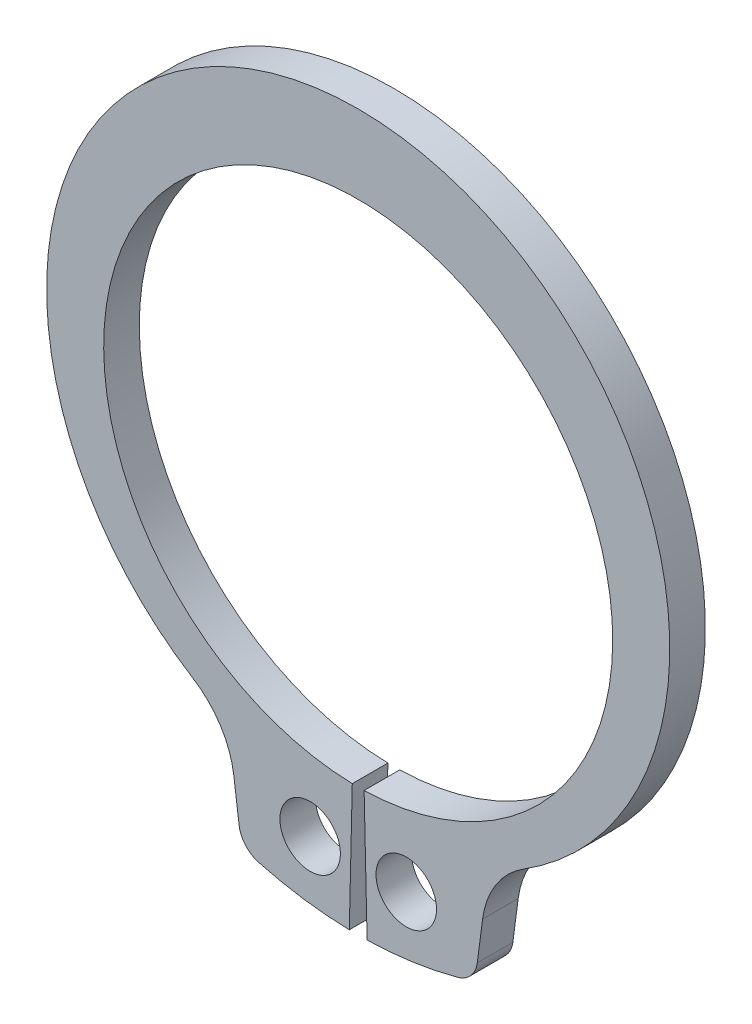
SolidWorks part; units mm, degrees
ref_plane "Plane1" through (0, 0, 0) normal (0, 0, 1) x (1, 0, 0)
ref_plane "Plane2" through (0, 0, 0) normal (0, 1, 0) x (1, 0, 0)
ref_plane "Plane3" through (0, 0, 0) normal (1, 0, 0) x (0, 0, -1)
sketch "Clipboard" plane through (0, 0, 0) normal (0, 0, 1) x (1, 0, 0)
  line L0 (0, 0) -> (2.2, 0)
  line L1 (0, 0) -> (0, 1.1)
  line L2 (0, 0) -> (0, -3.6)
  circle A0 centre (0, 0) radius 0.85
  circle A1 centre (0, 0) radius 7.5
  dimension "HoleDia" = 1.7
  dimension "ShaftDia" = 15
  dimension "LargeSection" = 2.2
  dimension "SmallSection" = 1.1
  dimension "LugSection" = 3.6
sketch "BodySke" plane through (0, 0, 0) normal (0, 0, 1) x (1, 0, 0)
  line L0 (-1.5431, 0) -> (1.5431, 0) construction
  line L1 (0, 0) -> (0, 9.35) construction
  line L2 (0.1663, -7.1481) -> (0.25, -10.7471)
  line L3 (-0.1663, -7.1481) -> (-0.25, -10.7471)
  line L4 (0, 0) -> (5.972, -8.9385) construction
  line L5 (0, 0) -> (-5.972, -8.9385) construction
  line L7 (3.4948, -8.6124) -> (3.3446, -9.7537)
  line L8 (-3.4948, -8.6124) -> (-3.3446, -9.7537)
  circle A0 centre (0, 0) radius 7.15 construction
  arc A1 (0.1663, -7.1481) -> (-0.1663, -7.1481) centre (0, 0) ccw
  arc A2 (4.5832, -6.8598) -> (-4.5832, -6.8598) centre (0, 0.5972) ccw construction
  arc A3 (0.25, -10.7471) -> (2.7961, -10.38) centre (0, 0) ccw
  arc A4 (4.6458, -6.8209) -> (3.4948, -8.6124) centre (5.972, -8.9385) ccw
  arc A5 (-3.4948, -8.6124) -> (-4.6458, -6.8209) centre (-5.972, -8.9385) ccw
  arc A6 (-2.7961, -10.38) -> (-0.25, -10.7471) centre (0, 0) ccw
  arc A7 (4.6458, -6.8209) -> (-4.6458, -6.8209) centre (0, 0.5972) ccw
  arc A8 (-3.5203, -8.4186) -> (3.5203, -8.4186) centre (0, 0) ccw construction
  circle A9 centre (1.35, -9.0246) radius 0.85
  circle A10 centre (-1.35, -9.0246) radius 0.85
  arc A11 (3.3446, -9.7537) -> (2.7961, -10.38) centre (2.601, -9.6558) cw
  arc A12 (-3.3446, -9.7537) -> (-2.7961, -10.38) centre (-2.601, -9.6558) ccw
  point P28 (3.2809, -10.2371)
  point P31 (-3.2809, -10.2371)
  dimension "GrooveDia" = 14.3
  dimension "D3" = 0.75
  dimension "LugRad" = 10.75
  dimension "HoleOffsetRad" = 9.125
  dimension "HoleDia" = 1.7
  dimension "D2" = 15
  dimension "LargeRad" = 9.35
  dimension "SmallRad" = 8.25
  dimension "Gap" = 0.5
  dimension "SmallAngle" = 67.496
  dimension "HoleSpacing" = 2.7
extrude "Body" add sketch "BodySke" against normal blind 1
sketch "NotSke" plane through (0, 0, 0) normal (0, 0, 1) x (1, 0, 0)
  line L0 (1.35, -8.1746) -> (1.35, -9.8746)
  line L1 (1.35, -9.8746) -> (-1.35, -9.8746)
  line L2 (-1.35, -9.8746) -> (-1.35, -8.1746)
  line L3 (-1.35, -8.1746) -> (1.35, -8.1746)
  circle A0 centre (1.35, -9.0246) radius 0.85 construction
  circle A1 centre (-1.35, -9.0246) radius 0.85 construction
extrude "Notch" [suppressed] cut sketch "NotSke" against normal through all
sketch "UnlSke" plane through (0, 0, 0) normal (0, 0, 1) x (1, 0, 0)
  line L0 (-2.5738, -10.4373) -> (-1.7119, -6.942)
  line L1 (2.5738, -10.4373) -> (1.7119, -6.942)
  arc A0 (1.7119, -6.942) -> (-1.7119, -6.942) centre (0, 0) ccw
  arc A1 (2.5738, -10.4373) -> (-2.5738, -10.4373) centre (0, 0) ccw
  arc A2 (0.25, -10.7471) -> (2.7961, -10.38) centre (0, 0) ccw construction
  arc A3 (0.1663, -7.1481) -> (-0.1663, -7.1481) centre (0, 0) ccw construction
  circle A4 centre (-1.35, -9.0246) radius 0.85 construction
  circle A5 centre (1.35, -9.0246) radius 0.85 construction
extrude "Unlug" [suppressed] add sketch "UnlSke" against normal through all
equation "' \"ShaftDia@Clipboard\" = 3"
equation "' \"Thickness@Body\" = 0.4"
equation "' \"GrooveDia@BodySke\" = 2.8"
equation "' \"LugSection@Clipboard\" = 1.9"
equation "' \"LargeSection@Clipboard\" = 0.8"
equation "' \"HoleDia@Clipboard\" = 1.0"
equation "' \"ShaftDia@Clipboard\" = 10"
equation "' \"Thickness@Body\" = 1.0"
equation "' \"GrooveDia@BodySke\" = 9.6"
equation "' \"LugSection@Clipboard\" = 3.3"
equation "' \"LargeSection@Clipboard\" = 1.8"
equation "' \"HoleDia@Clipboard\" = 1.5"
equation "\"SmallSection@Clipboard\" = \"LargeSection@Clipboard\" * 0.5"
equation "\"Gap@BodySke\" =  \"Thickness@Body\" / 2"
equation "\"LargeRad@BodySke\" =  \"GrooveDia@BodySke\" / 2 +  \"LargeSection@Clipboard\""
equation "\"SmallRad@BodySke\" =  \"GrooveDia@BodySke\" / 2 +  \"SmallSection@Clipboard\""
equation "\"LugRad@BodySke\" = \"GrooveDia@BodySke\" / 2 + \"LugSection@Clipboard\""
equation "\"HoleOffsetRad@BodySke\" = (  \"ShaftDia@Clipboard\" / 2 + \"LugRad@BodySke\" ) / 2"
equation "\"HoleSpacing@BodySke\" = \"Gap@BodySke\"  * 2 +  \"HoleDia@Clipboard\""
equation "\"HoleDia@BodySke\" =  \"HoleDia@Clipboard\""
equation "\"SmallAngle@BodySke\" = atn(\"HoleSpacing@BodySke\" / 2 / sqr(\"HoleOffsetRad@BodySke\"  * \"HoleOffsetRad@BodySke\" - (\"HoleSpacing@BodySke\" / 2) * (\"HoleSpacing@BodySke\" / 2) ))  * 7 *  (\"LargeRad@BodySke\" / \"SmallRad@BodySke\")* ( 180 / 3.141593)"
